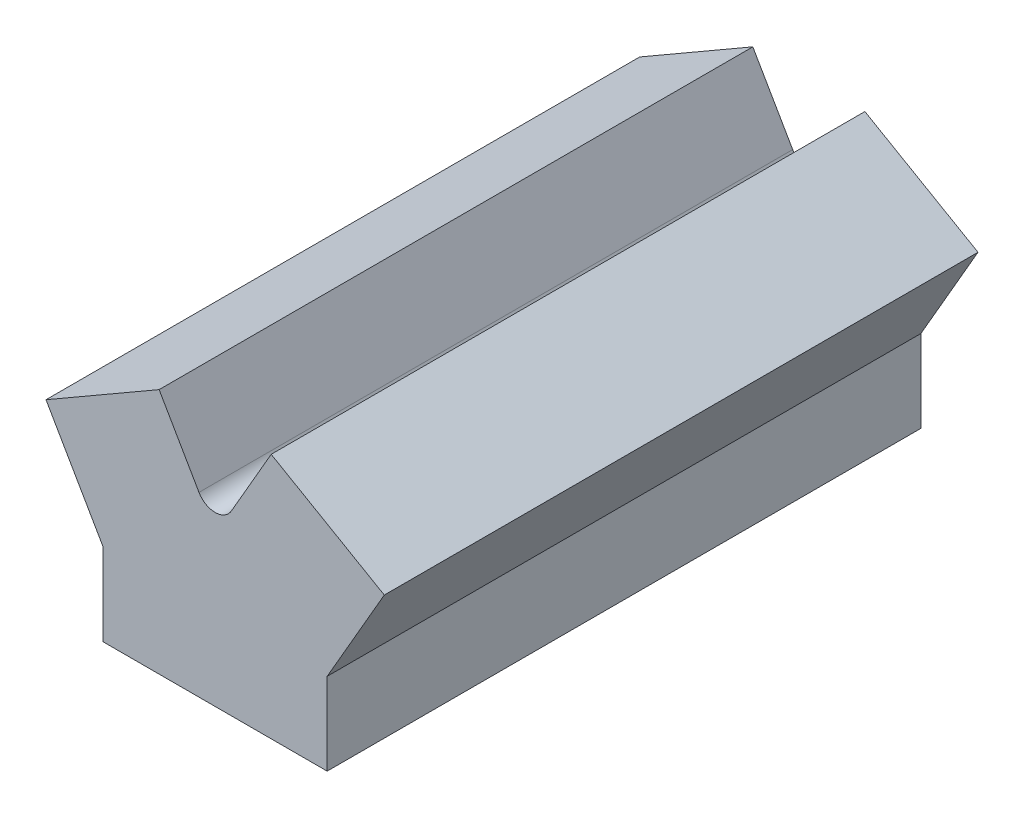
SolidWorks part; units mm, degrees
ref_plane "Front Plane" through (0, 0, 0) normal (0, 0, 1) x (1, 0, 0)
ref_plane "Top Plane" through (0, 0, 0) normal (0, 1, 0) x (1, 0, 0)
ref_plane "Right Plane" through (0, 0, 0) normal (1, 0, 0) x (0, 0, -1)
sketch "Sketch1" plane through (0, 0, 0) normal (0, 0, 1) x (1, 0, 0)
  line L0 (-10.9985, 120.65) -> (-38.1141, 167.6156)
  line L1 (-38.1141, 167.6156) -> (-115.0614, 123.19)
  line L2 (-115.0614, 123.19) -> (-76.2, 55.88)
  line L3 (-76.2, 55.88) -> (-76.2, 0)
  line L4 (-76.2, 0) -> (76.2, 0)
  line L5 (76.2, 0) -> (76.2, 55.88)
  line L6 (76.2, 55.88) -> (115.0614, 123.19)
  line L7 (115.0614, 123.19) -> (38.1141, 167.6156)
  line L8 (38.1141, 167.6156) -> (10.9985, 120.65)
  line L9 (0, 0) -> (0, 193.5084) construction
  arc A0 (-10.9985, 120.65) -> (10.9985, 120.65) centre (0, 127) ccw
  point P15 (0, 0)
  point P16 (0, 0)
  point P17 (0, 0)
  dimension "D1" = 25.4
  dimension "D2" = 127
  dimension "D3" = 90
  dimension "D4" = 30
  dimension "D5" = 30
  dimension "D6" = 123.19
  dimension "D7" = 55.88
  dimension "D8" = 152.4
extrude "Boss-Extrude1" add sketch "Sketch1" along normal blind 403.86
sketch "Sketch2" plane through (0, 0, 403.86) normal (0, 0, 1) x (1, 0, 0)
  line L0 (26.3115, 45.814) -> (50.8, 31.75)
  line L1 (50.8, 31.75) -> (50.8, 0)
  line L2 (-76.2, 0) -> (76.2, 0) construction
  line L3 (50.8, 0) -> (-50.8, 0)
  line L4 (-50.8, 0) -> (-50.8, 31.75)
  line L5 (-50.8, 31.75) -> (-26.3115, 45.814)
  line L6 (76.2, 0) -> (76.2, 55.88) construction
  arc A0 (26.3115, 45.814) -> (-26.3115, 45.814) centre (0, 0) ccw
  point P11 (0, 0)
  point P12 (0, 0)
  point P13 (0, 0)
  dimension "D1" = 105.664
  dimension "D2" = 31.75
  dimension "D3" = 25.4
extrude "Cut-Extrude2" cut sketch "Sketch2" against normal blind 353.06 from offset 25.4 offset against normal yes
sketch "Sketch3" plane through (82.1082, 142.2156, 0) normal (0.5, 0.866, 0) x (0.866, -0.5, 0)
  line L0 (0, 0) -> (0, -403.86) construction
  line L1 (38.0511, -403.86) -> (-50.8, -403.86) construction
  circle A0 centre (0, -60.96) radius 22.86
  circle A1 centre (0, -172.72) radius 22.86
  circle A2 centre (0, -284.48) radius 22.86
  dimension "D1" = 45.72
  dimension "D3" = 111.76
  dimension "D2" = 60.96
  dimension "D4" = 111.76
extrude "Cut-Extrude5" cut sketch "Sketch3" against normal blind 353.06 from offset 19.05 contours A2 | A1 | A0 offset against normal yes
sketch "Sketch4" plane through (-82.1082, 142.2156, 0) normal (-0.5, 0.866, 0) x (0.866, 0.5, 0)
  line L0 (0, 0) -> (0, -403.86) construction
  line L1 (50.8, -403.86) -> (-38.0511, -403.86) construction
  circle A0 centre (0, -340.36) radius 22.86
  circle A1 centre (0, -228.6) radius 22.86
  circle A2 centre (0, -116.84) radius 22.86
  point P11 (0, 0)
  point P13 (-31.3883, -325.07)
  dimension "D1" = 45.72
  dimension "D2" = 63.5
  dimension "D3" = 111.76
  dimension "D4" = 111.76
extrude "Cut-Extrude6" cut sketch "Sketch4" against normal blind 353.06 from offset 19.05 contours A0 | A1 | A2 offset against normal yes
sketch "Sketch5" plane through (0, 0, 0) normal (0, -1, 0) x (1, 0, 0)
  line L0 (-50.8, 378.46) -> (50.8, 378.46) construction
  line L1 (50.8, 25.4) -> (50.8, 378.46) construction
  line L3 (-50.8, 25.4) -> (-50.8, 378.46) construction
  line L4 (-50.8, 25.4) -> (50.8, 25.4) construction
  circle A0 centre (-63.5, 12.7) radius 5.715
  circle A1 centre (63.5, 391.16) radius 5.715
  dimension "D1" = 11.43
  dimension "D2" = 11.43
  dimension "D3" = 12.7
  dimension "D4" = 12.7
  dimension "D5" = 12.7
  dimension "D6" = 12.7
extrude "Cut-Extrude7" cut sketch "Sketch5" against normal blind 76.2 contours A0 | A1
